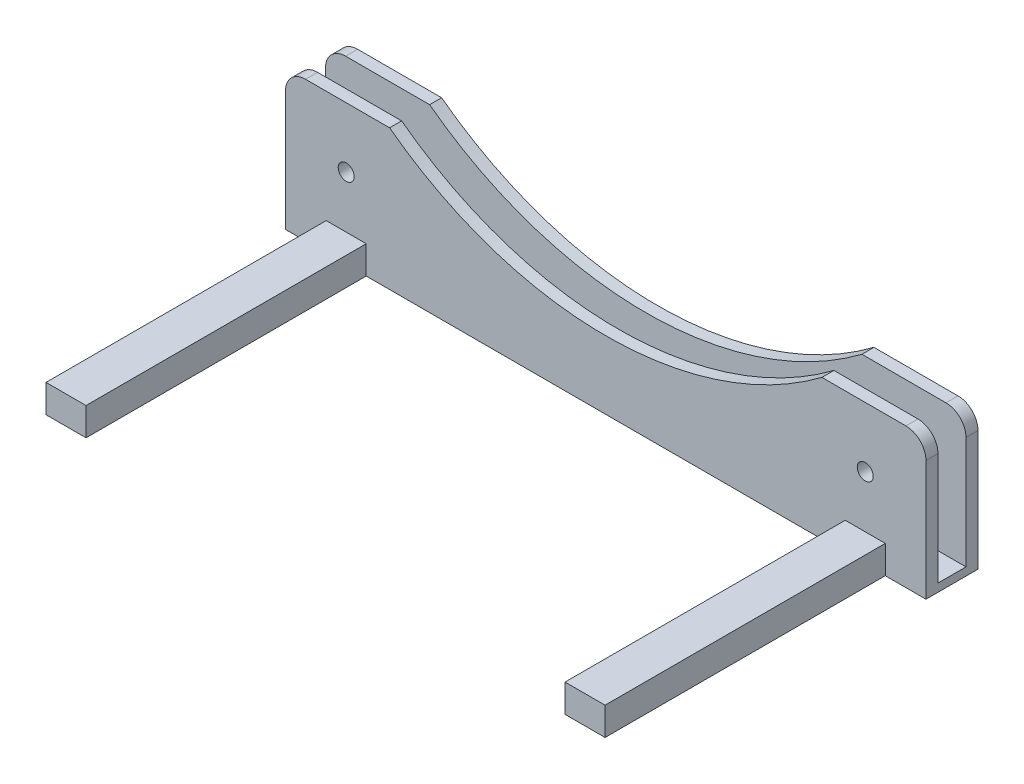
SolidWorks part; units mm, degrees
ref_plane "前视基准面" through (0, 0, 0) normal (0, 0, 1) x (1, 0, 0)
ref_plane "上视基准面" through (0, 0, 0) normal (0, 1, 0) x (1, 0, 0)
ref_plane "右视基准面" through (0, 0, 0) normal (1, 0, 0) x (0, 0, -1)
sketch "草图1" plane through (0, 0, 0) normal (0, 0, 1) x (1, 0, 0)
  line L0 (0, 0) -> (0, -148.0216) construction
  line L1 (54, -72) -> (75, -72)
  line L2 (-75, -72) -> (-54, -72)
  line L3 (-80, -77) -> (-80, -107)
  line L4 (-80, -107) -> (80, -107)
  line L5 (80, -77) -> (80, -107)
  circle A0 centre (0, 0) radius 100 construction
  circle A1 centre (64.8325, -87) radius 8.5 construction
  circle A2 centre (-64.8325, -87) radius 8.5 construction
  circle A3 centre (-64.8325, -87) radius 2
  circle A4 centre (64.8325, -87) radius 2
  arc A5 (-54, -72) -> (54, -72) centre (0, 0) ccw
  arc A6 (75, -72) -> (80, -77) centre (75, -77) cw
  arc A7 (-75, -72) -> (-80, -77) centre (-75, -77) ccw
  point P18 (80, -72)
  dimension "D1" = 200
  dimension "D2" = 17
  dimension "D5" = 4
  dimension "D6" = 4
  dimension "D7" = 107
  dimension "D9" = 180
  dimension "D10" = 5
  dimension "D3" = 20
  dimension "D4" = 160
  dimension "D8" = 35
extrude "凸台-拉伸1" add sketch "草图1" along normal blind 13
sketch "草图2" plane through (80, 0, 0) normal (1, 0, 0) x (0, 0, -1)
  line L0 (-6.5, -72) -> (-6.5, -50072) construction
  line L1 (-13, -72) -> (0, -72) construction
  line L2 (-13, -107) -> (-13, -77) construction
  line L3 (-10, -70.1586) -> (-3, -70.1586)
  line L4 (-10, -70.1586) -> (-10, -105)
  line L5 (-10, -105) -> (-3, -105)
  line L6 (-3, -70.1586) -> (-3, -105)
  line L7 (0, -77) -> (0, -72) construction
  line L8 (-13, -107) -> (0, -107) construction
  point P4 (-6.5, -72)
  dimension "D1" = 3
  dimension "D2" = 3
  dimension "D3" = 2
  dimension "D4" = 7
extrude "切除-拉伸1" cut sketch "草图2" against normal through all
sketch "草图3" plane through (0, 0, 13) normal (0, 0, 1) x (1, 0, 0)
  line L0 (0, -107) -> (0, 49893) construction
  line L1 (-69.8325, -107) -> (-59.8325, -107)
  line L2 (-69.8325, -107) -> (-69.8325, -100)
  line L3 (-69.8325, -100) -> (-59.8325, -100)
  line L4 (-59.8325, -107) -> (-59.8325, -100)
  line L5 (-80, -107) -> (80, -107) construction
  line L6 (-64.8325, -87) -> (-64.8325, -120.5701) construction
  line L7 (-69.8325, -107) -> (-69.8325, -100)
  line L8 (-59.8325, -107) -> (-59.8325, -100)
  line L9 (-69.8325, -107) -> (-69.8325, -100)
  line L10 (-59.8325, -107) -> (-59.8325, -100)
  line L11 (-69.8325, -107) -> (-69.8325, -100)
  line L12 (-59.8325, -107) -> (-59.8325, -100)
  line L13 (69.8325, -107) -> (59.8325, -107)
  line L14 (59.8325, -107) -> (59.8325, -100)
  line L15 (69.8325, -100) -> (59.8325, -100)
  line L16 (69.8325, -107) -> (69.8325, -100)
  point P9 (0, -107)
  line M9 (-80, -107) -> (80, -107)
  dimension "D1" = 7
  dimension "D2" = 10
extrude "凸台-拉伸2" add sketch "草图3" along normal blind 70 contours L4 L3 L2 M9 | L16 L15 L14 M9
